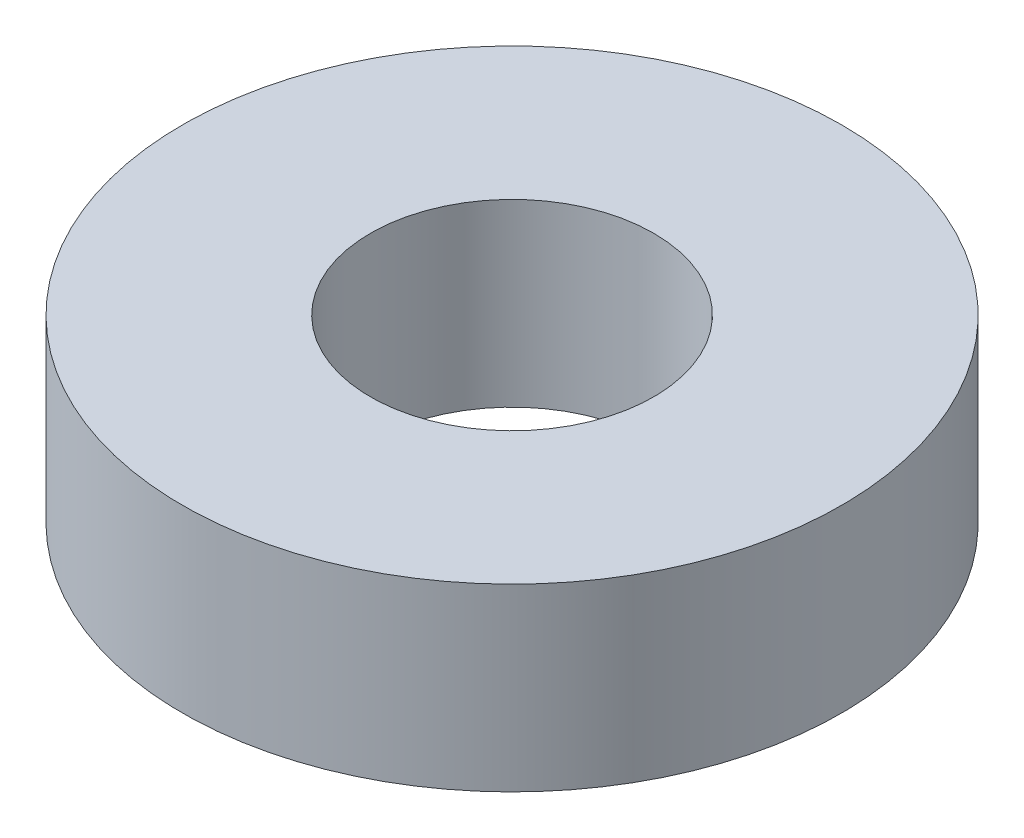
SolidWorks part; units mm, degrees
material "1023 Karbon Çeliği Levha (SS)"
ref_plane "Ön Düzlem" through (0, 0, 0) normal (0, 0, 1) x (1, 0, 0)
ref_plane "Üst Düzlem" through (0, 0, 0) normal (0, 1, 0) x (1, 0, 0)
ref_plane "Sağ Düzlem" through (0, 0, 0) normal (1, 0, 0) x (0, 0, -1)
sketch "Çizim2" plane through (0, 0, 0) normal (0, 1, 0) x (1, 0, 0)
  circle A0 centre (0, 0) radius 5.985
  circle A1 centre (0, 0) radius 13.92
extrude "Yükseklik-Ekstrüzyon1" add sketch "Çizim2" along normal blind 7.6
